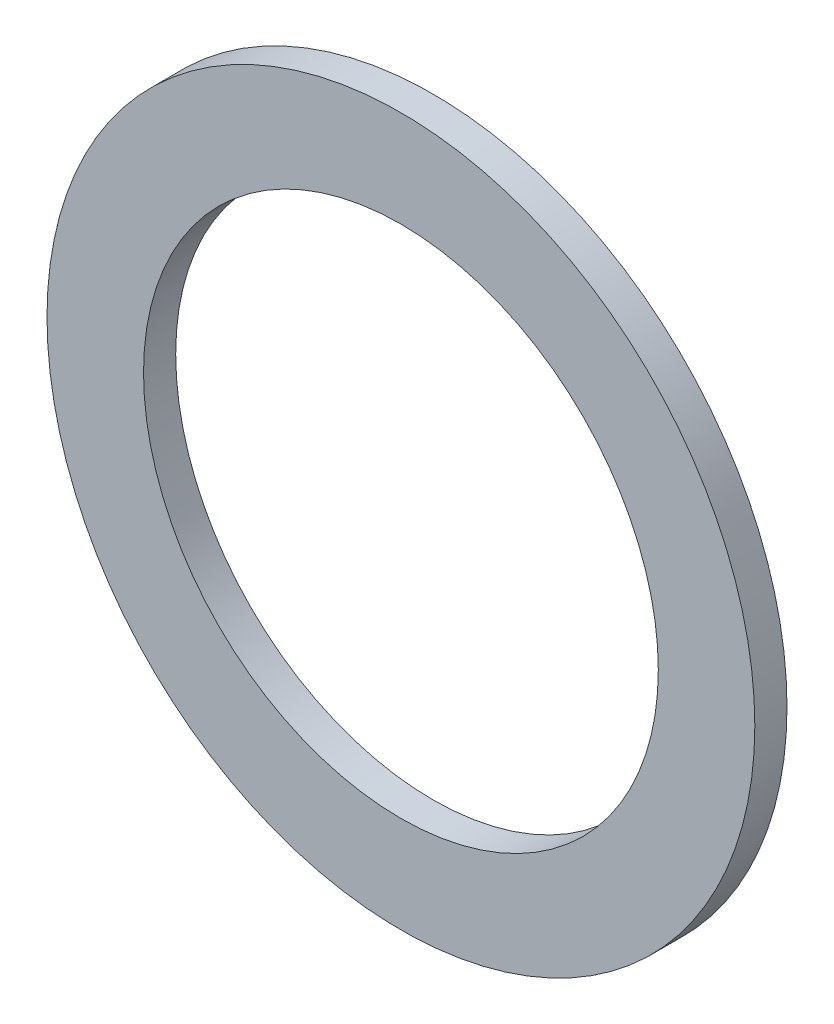
SolidWorks part; units mm, degrees
material "Brass"
ref_plane "Front Plane" through (0, 0, 0) normal (0, 0, 1) x (1, 0, 0)
ref_plane "Top Plane" through (0, 0, 0) normal (0, 1, 0) x (1, 0, 0)
ref_plane "Right Plane" through (0, 0, 0) normal (1, 0, 0) x (0, 0, -1)
sketch "Sketch1" plane through (0, 0, 0) normal (0, 0, 1) x (1, 0, 0)
  circle A0 centre (0, 0) radius 2.75
  circle A1 centre (0, 0) radius 2
  dimension "OD" = 5.5
  dimension "ID1" = 4
extrude "Boss-Extrude1" add sketch "Sketch1" along normal blind 0.25
